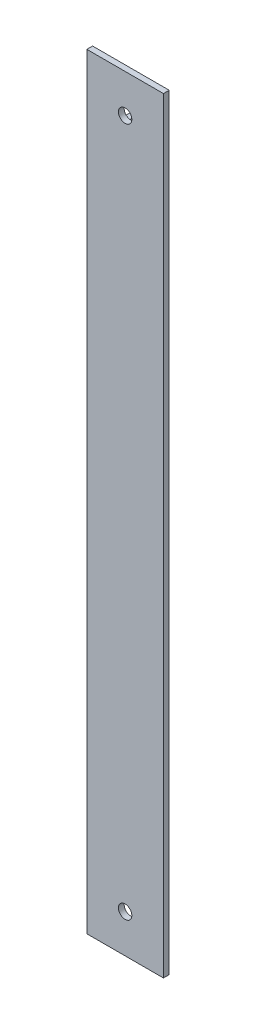
SolidWorks part; units mm, degrees
ref_plane "Спереди" through (0, 0, 0) normal (0, 0, 1) x (1, 0, 0)
ref_plane "Сверху" through (0, 0, 0) normal (0, 1, 0) x (1, 0, 0)
ref_plane "Справа" through (0, 0, 0) normal (1, 0, 0) x (0, 0, -1)
sketch "Эскиз1" plane through (0, 0, 0) normal (0, 1, 0) x (1, 0, 0)
  line L0 (0, 0) -> (0, 20)
  line L1 (0, 20) -> (1.5, 20)
  line L2 (1.5, 20) -> (1.5, 1.5)
  line L3 (1.5, 1.5) -> (20, 1.5)
  line L4 (20, 1.5) -> (20, 0)
  line L5 (20, 0) -> (0, 0)
  point P4 (0, 0)
  point P8 (0, 0)
  dimension "D1" = 20
  dimension "D2" = 1.5
extrude "Бобышка-Вытянуть1" add sketch "Эскиз1" along normal blind 200
sketch "Эскиз2" plane through (0, 200, 0) normal (0, 1, 0) x (1, 0, 0)
  line L1 (0, 20) -> (1.5, 20)
  line L2 (0, 20) -> (0, 1.5)
  line L3 (0, 1.5) -> (1.5, 1.5)
  line L4 (1.5, 20) -> (1.5, 1.5)
extrude "Вырез-Вытянуть1" cut sketch "Эскиз2" against normal blind 20
ref_plane "Плоскость1" through (0, 100, 0) normal (0, -1, 0) x (-1, 0, 0)
sketch "Эскиз3" plane through (0, 0, 0) normal (0, 0, 1) x (1, 0, 0)
  line L0 (0, 200) -> (20, 200) construction
  circle A0 centre (10, 190) radius 1.75
  point P2 (0, 0)
  point P5 (10, 200)
  dimension "D1" = 3.5
  dimension "D2" = 10
extrude "Вырез-Вытянуть2" cut sketch "Эскиз3" against normal up to next
mirror "Зеркальное отражение1" about plane through (0, 100, 0) normal (0, -1, 0) of "Вырез-Вытянуть2", "Вырез-Вытянуть1"
equation "\"ATX.Case.01.Dimension.3\"=200"
equation "\"ATX.Case.01.Profile.20.Width\"=20"
equation "\"ATX.Case.01.Profile.20.Thickness\" = 1.5"
equation "\"D1@Эскиз1\"= \"ATX.Case.01.Profile.20.Width\""
equation "\"D2@Эскиз1\"= \"ATX.Case.01.Profile.20.Thickness\""
equation "\"D1@Бобышка-Вытянуть1\"= \"ATX.Case.01.Dimension.3\""
equation "\"D1@Вырез-Вытянуть1\"= \"ATX.Case.01.Profile.20.Width\""
equation "\"D2@Эскиз3\"= \"ATX.Case.01.Profile.20.Width\" / 2"
